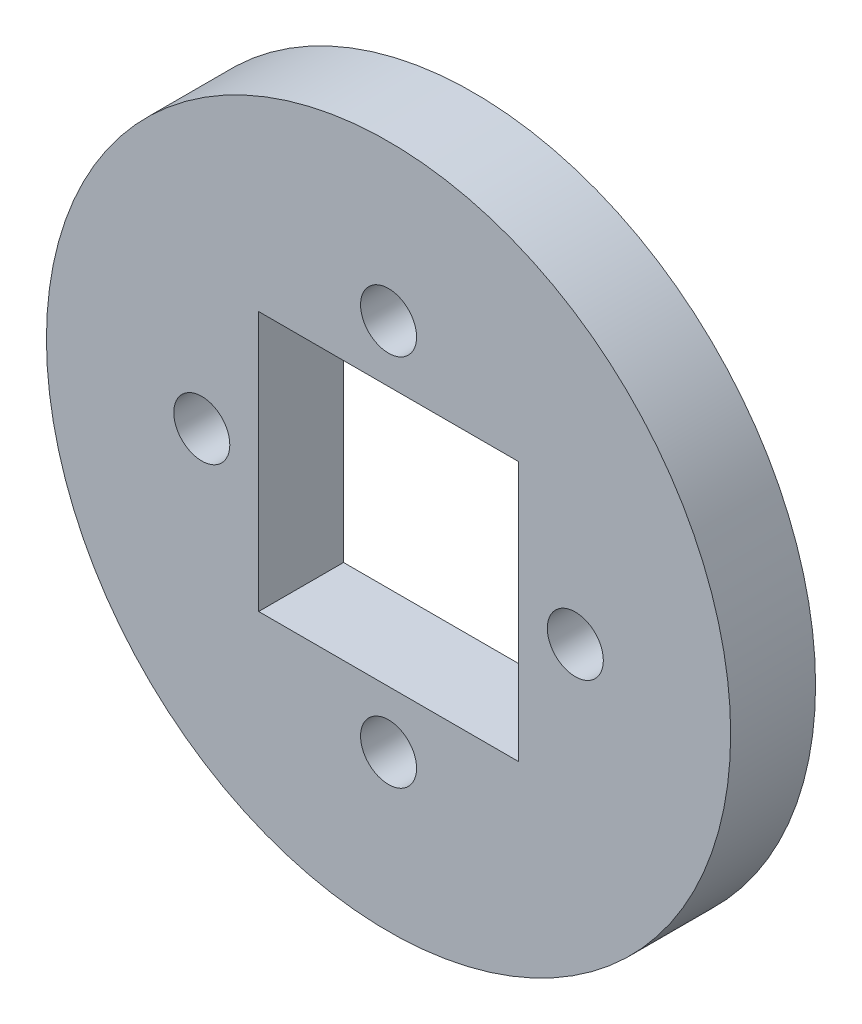
SolidWorks part; units mm, degrees
ref_plane "Front Plane" through (0, 0, 0) normal (0, 0, 1) x (1, 0, 0)
ref_plane "Top Plane" through (0, 0, 0) normal (0, 1, 0) x (1, 0, 0)
ref_plane "Right Plane" through (0, 0, 0) normal (1, 0, 0) x (0, 0, -1)
sketch "Sketch1" plane through (0, 0, 0) normal (0, 0, 1) x (1, 0, 0)
  line L0 (-15.3, 15.3) -> (-15.3, -15.3) construction
  line L1 (-15.3, -15.3) -> (15.3, -15.3) construction
  line L2 (15.3, -15.3) -> (15.3, 15.3) construction
  line L3 (15.3, 15.3) -> (-15.3, 15.3) construction
  line L4 (-15.3, 15.3) -> (-15.3, -15.3)
  line L5 (-15.3, -15.3) -> (15.3, -15.3)
  line L6 (15.3, -15.3) -> (15.3, 15.3)
  line L7 (15.3, 15.3) -> (-15.3, 15.3)
  arc A0 (-35.9137, 18.2838) -> (17.6382, 36.2351) centre (0, 0) ccw construction
  arc A1 (-35.9137, 18.2838) -> (17.6382, 36.2351) centre (0, 0) ccw construction
  circle A2 centre (0, 0) radius 40.3
  circle A3 centre (0, 22) radius 1.65
  circle A4 centre (22, 0) radius 1.65
  circle A5 centre (0, -22) radius 1.65
  circle A6 centre (-22, 0) radius 1.65
  dimension "D1" = 3.3
extrude "Boss-Extrude1" add sketch "Sketch1" along normal blind 10
sketch "Sketch2" plane through (0, 0, 10) normal (0, 0, 1) x (1, 0, 0)
  circle A0 centre (22, 0) radius 3.3
  circle A1 centre (0, 22) radius 3.3
  circle A2 centre (-22, 0) radius 3.3
  circle A3 centre (0, -22) radius 3.3
  dimension "D1" = 6.6
extrude "Cut-Extrude1" cut sketch "Sketch2" against normal blind 6
